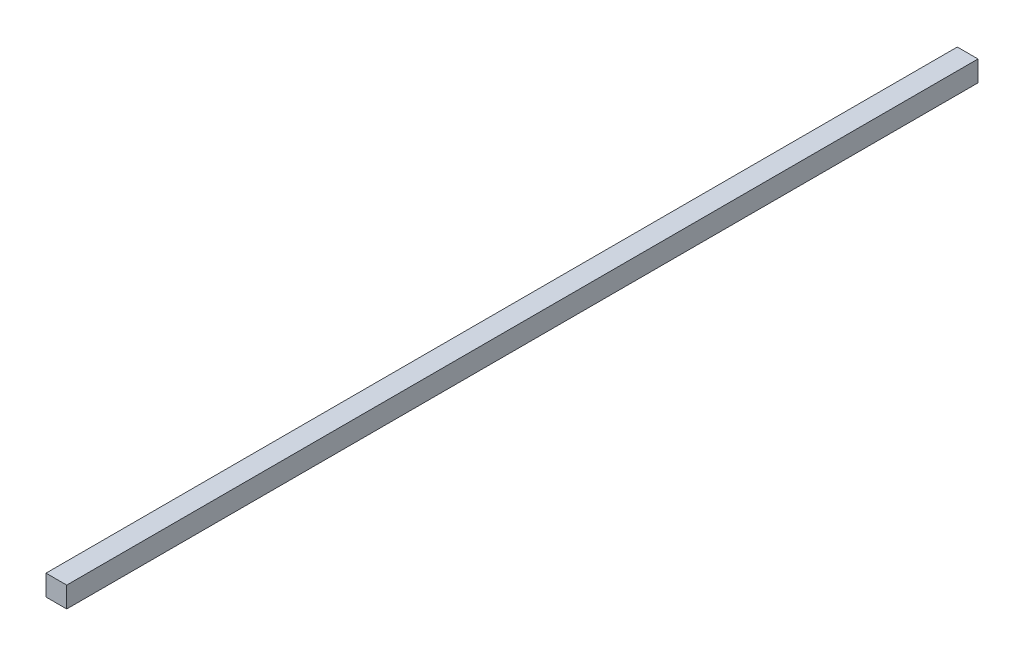
SolidWorks part; units mm, degrees
ref_plane "Front Plane" through (0, 0, 0) normal (0, 0, 1) x (1, 0, 0)
ref_plane "Top Plane" through (0, 0, 0) normal (0, 1, 0) x (1, 0, 0)
ref_plane "Right Plane" through (0, 0, 0) normal (1, 0, 0) x (0, 0, -1)
sketch "Sketch1" plane through (0, 0, 0) normal (0, 0, 1) x (1, 0, 0)
  line L1 (-5, 5) -> (5, 5)
  line L2 (-5, 5) -> (-5, -5)
  line L3 (-5, -5) -> (5, -5)
  line L4 (5, 5) -> (5, -5)
  line L5 (-5, 5) -> (5, -5) construction
  line L6 (-5, -5) -> (5, 5) construction
  point P0 (0, 0)
  dimension "D1" = 10
  dimension "D2" = 10
extrude "Boss-Extrude1" add sketch "Sketch1" along normal blind 440
